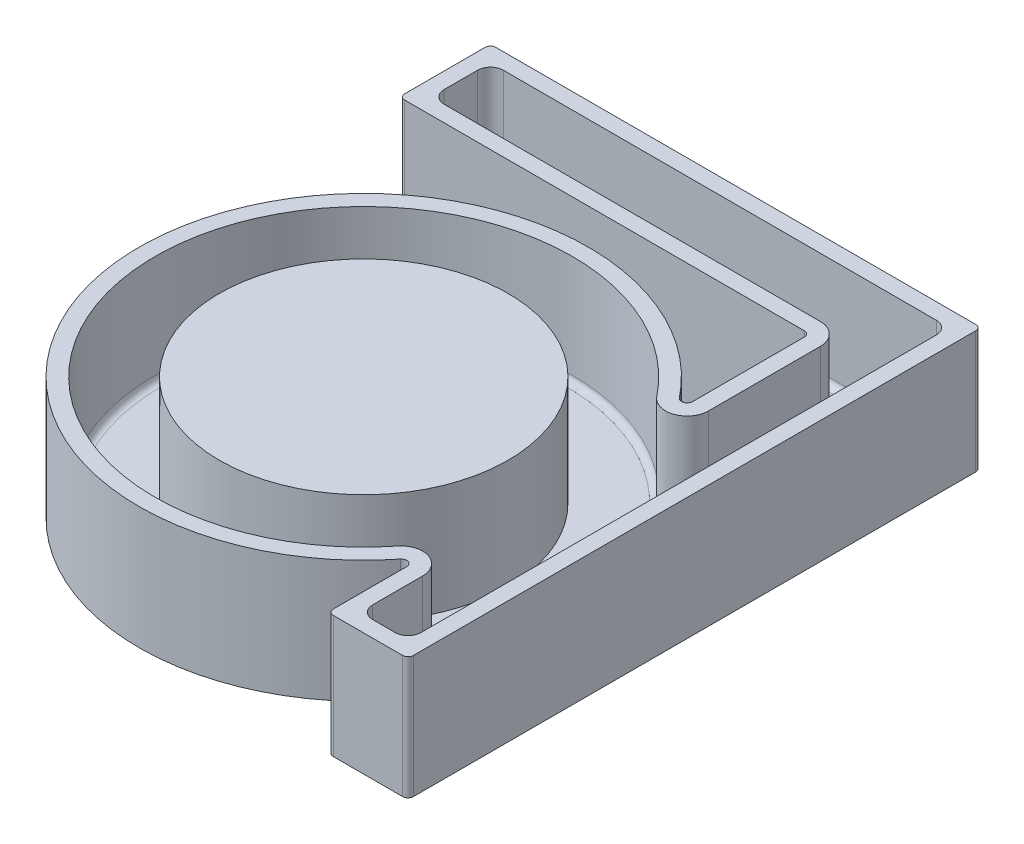
SolidWorks part; units mm, degrees
ref_plane "Front Plane" through (0, 0, 0) normal (0, 0, 1) x (1, 0, 0)
ref_plane "Top Plane" through (0, 0, 0) normal (0, 1, 0) x (1, 0, 0)
ref_plane "Right Plane" through (0, 0, 0) normal (1, 0, 0) x (0, 0, -1)
sketch "Sketch1" plane through (0, 0, 0) normal (0, 1, 0) x (1, 0, 0)
  line L0 (30.603, -26.5638) -> (41.396, -26.5638)
  line L1 (41.396, 62.7296) -> (-33.347, 62.7296)
  line L2 (42.2495, 61.8761) -> (42.2495, 54.2897)
  line L3 (28.896, 48.5226) -> (-33.347, 48.5226)
  line L4 (-34.2005, 61.8761) -> (-34.2005, 49.3761)
  line L5 (29.7495, -14.2766) -> (29.7495, -25.7103)
  line L8 (29.7495, 47.6691) -> (29.7495, 30.2559)
  line L10 (42.2495, 54.2897) -> (42.2495, -25.7103)
  arc A0 (28.227, 29.7259) -> (28.227, -13.7465) centre (0.7946, 7.9897) ccw
  arc A1 (30.603, -26.5638) -> (29.7495, -25.7103) centre (30.603, -25.7103) cw
  arc A2 (41.396, -26.5638) -> (42.2495, -25.7103) centre (41.396, -25.7103) ccw
  arc A3 (-33.347, 48.5226) -> (-34.2005, 49.3761) centre (-33.347, 49.3761) cw
  arc A4 (-33.347, 62.7296) -> (-34.2005, 61.8761) centre (-33.347, 61.8761) ccw
  arc A5 (41.396, 62.7296) -> (42.2495, 61.8761) centre (41.396, 61.8761) cw
  arc A6 (28.896, 48.5226) -> (29.7495, 47.6691) centre (28.896, 47.6691) cw
  arc A7 (28.227, -13.7465) -> (29.7495, -14.2766) centre (28.896, -14.2766) cw
  arc A8 (28.227, 29.7259) -> (29.7495, 30.2559) centre (28.896, 30.2559) ccw
  point P2 (6.8397, 56.6096)
  point P7 (35.7946, 7.9897)
  point P20 (-34.2005, 62.7296)
  point P23 (42.2495, 62.7296)
  point P28 (29.7495, -11.6728)
  dimension "D1" = 70
  dimension "D2" = 0.8535
  dimension "D3" = 74.743
  dimension "D4" = 80
  dimension "D5" = 12.5
  dimension "D6" = 12.5
extrude "Boss-Extrude1" add sketch "Sketch1" along normal blind 19.05
sketch "Sketch2" plane through (0, 19.05, 0) normal (0, 1, 0) x (1, 0, 0)
  line L19 (39.7495, -24.0638) -> (39.7495, 60.2296)
  line L20 (39.7495, 60.2296) -> (-31.7005, 60.2296)
  line L21 (-31.7005, 60.2296) -> (-31.7005, 51.0226)
  line L22 (-31.7005, 51.0226) -> (28.896, 51.0226)
  line L23 (32.2495, 47.6691) -> (32.2495, 30.2559)
  line L24 (32.2495, -14.2766) -> (32.2495, -24.0638)
  line L25 (32.2495, -24.0638) -> (39.7495, -24.0638)
  line L26 (39.7495, -24.0638) -> (39.7495, 60.2296)
  line L27 (39.7495, 60.2296) -> (-31.7005, 60.2296)
  line L28 (-31.7005, 60.2296) -> (-31.7005, 51.0226)
  line L29 (-31.7005, 51.0226) -> (28.896, 51.0226)
  line L30 (32.2495, 47.6691) -> (32.2495, 30.2559)
  line L31 (32.2495, -14.2766) -> (32.2495, -24.0638)
  line L32 (32.2495, -24.0638) -> (39.7495, -24.0638)
  circle A10 centre (0.7946, 7.9897) radius 22.5
  arc A19 (32.2495, 47.6691) -> (28.896, 51.0226) centre (28.896, 47.6691) ccw
  arc A20 (26.2676, 28.1733) -> (32.2495, 30.2559) centre (28.896, 30.2559) ccw
  arc A21 (26.2676, 28.1733) -> (26.2676, -12.1939) centre (0.7946, 7.9897) ccw
  arc A22 (32.2495, -14.2766) -> (26.2676, -12.1939) centre (28.896, -14.2766) ccw
  arc A23 (32.2495, 47.6691) -> (28.896, 51.0226) centre (28.896, 47.6691) ccw
  arc A24 (26.2676, 28.1733) -> (32.2495, 30.2559) centre (28.896, 30.2559) ccw
  arc A25 (26.2676, 28.1733) -> (26.2676, -12.1939) centre (0.7946, 7.9897) ccw
  arc A26 (32.2495, -14.2766) -> (26.2676, -12.1939) centre (28.896, -14.2766) ccw
  dimension "D2" = 45
  dimension "D1" = 2.5
extrude "Cut-Extrude1" cut sketch "Sketch2" against normal blind 17.05
fillet "Fillet1" radius 2 5 edges at (32.2495, 10.525, 24.0638) (39.7495, 10.525, 24.0638) (-31.7005, 10.525, -51.0226) (-31.7005, 10.525, -60.2296) (39.7495, 10.525, -60.2296)
fillet "Fillet2" radius 1 16 edges at (29.9986, 2, 11.1095) (-31.7054, 2, -7.9897) (29.9986, 2, -27.0889) (32.2495, 2, -38.9625) (31.2673, 2, -50.0404) (-0.4023, 2, -51.0226) (-31.1147, 2, -51.6084) (-31.7005, 2, -55.6261) (-31.1147, 2, -59.6438) (4.0245, 2, -60.2296) (39.1637, 2, -59.6438) (39.7495, 2, -18.0829) (39.1637, 2, 23.478) (35.9995, 2, 24.0638) (32.8353, 2, 23.478) (32.2495, 2, 18.1702)
